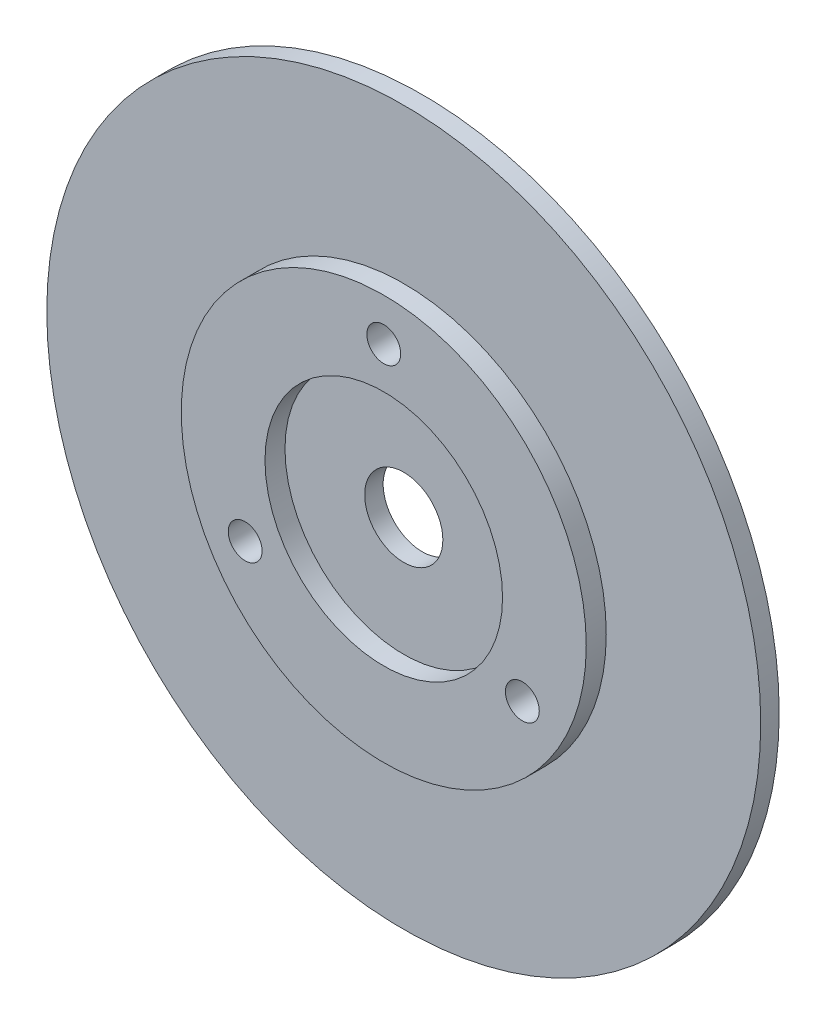
SolidWorks part; units mm, degrees
ref_plane "Front Plane" through (0, 0, 0) normal (0, 0, 1) x (1, 0, 0)
ref_plane "Top Plane" through (0, 0, 0) normal (0, 1, 0) x (1, 0, 0)
ref_plane "Right Plane" through (0, 0, 0) normal (1, 0, 0) x (0, 0, -1)
sketch "Sketch4" plane through (0, 0, 0) normal (0, 1, 0) x (1, 0, 0)
  line L1 (6.35, 0) -> (19.3, 0)
  line L2 (6.35, 0) -> (6.35, 3)
  line L3 (6.35, 3) -> (58, 3)
  line L4 (58, 0) -> (58, 3)
  line L5 (32.9, 0) -> (58, 0)
  line L7 (19.3, 0) -> (19.3, -3.25)
  line L8 (19.3, -3.25) -> (32.9, -3.25)
  line L9 (32.9, 0) -> (32.9, -3.25)
  line L10 (0, 0) -> (0, 22.1789) construction
  point P4 (0, 0)
  dimension "D1" = 12.95
  dimension "D2" = 13.6
  dimension "D3" = 3.25
  dimension "D4" = 58
  dimension "D5" = 3
  dimension "D6" = 6.35
revolve "Revolve1" add sketch "Sketch4" angle 360 about L10
sketch "Sketch5" plane through (0, 0, 3.25) normal (0, 0, 1) x (1, 0, 0)
  circle A0 centre (0, 0) radius 26 construction
  dimension "D1" = 52
hole_wizard "M5 Clearance Hole1" positions "Sketch10" profile "Sketch9" hole size "M5" standard "ANSI Metric" end condition through all
sketch "Sketch10" plane through (0, 0, 3.25) normal (0, 0, 1) x (1, 0, 0)
  line L0 (0, 0) -> (-22.5167, -13) construction
  line L3 (0, 0) -> (22.5167, -13) construction
  line L6 (0, 26) -> (0, 0) construction
  circle A0 centre (0, 0) radius 26 construction
  point P0 (0, 26)
  point P13 (-22.5167, -13)
  point P15 (22.5167, -13)
  dimension "D1" = 120
  dimension "D2" = 120
sketch "Sketch9" plane through (0, 26, 3.25) normal (1, 0, 0) x (0, -1, 0)
  line L0 (0, 0) -> (0, 6.25)
  line L1 (0, 6.25) -> (2.75, 6.25)
  line L2 (2.75, 6.25) -> (2.75, 0)
  line L5 (2.75, 0) -> (0, 0)
  line L11 (0, -6.35) -> (0, 107.95) construction
  dimension "Thru Hole Dia." = 5.5
  dimension "Thru Hole Depth" = 6.25
